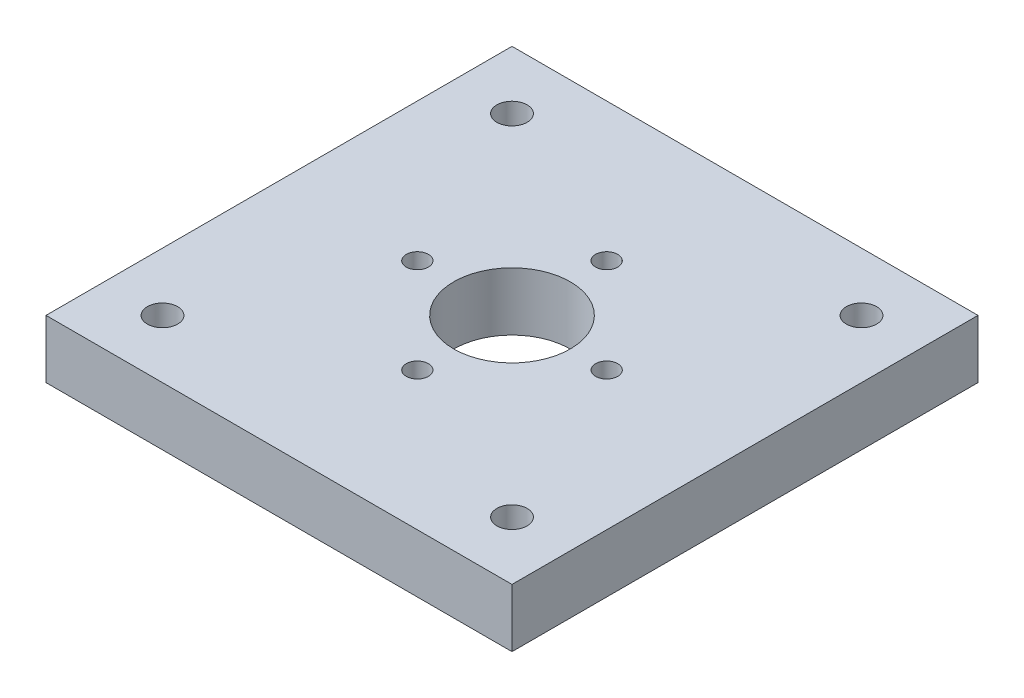
SolidWorks part; units mm, degrees
ref_plane "Front Plane" through (0, 0, 0) normal (0, 0, 1) x (1, 0, 0)
ref_plane "Top Plane" through (0, 0, 0) normal (0, 1, 0) x (1, 0, 0)
ref_plane "Right Plane" through (0, 0, 0) normal (1, 0, 0) x (0, 0, -1)
sketch "Sketch1" plane through (0, 0, 0) normal (0, 1, 0) x (1, 0, 0)
  line L0 (0, 24.4231) -> (0, -30.107) construction
  line L1 (-50.8, -50.8) -> (50.8, -50.8)
  line L2 (-50.8, -50.8) -> (-50.8, 50.8)
  line L3 (-50.8, 50.8) -> (50.8, 50.8)
  line L4 (50.8, -50.8) -> (50.8, 50.8)
  line L5 (-50.8, -50.8) -> (50.8, 50.8) construction
  line L6 (-50.8, 50.8) -> (50.8, -50.8) construction
  line L7 (-20.0713, 0) -> (21.8476, 0) construction
  circle A0 centre (-38.1, 38.1) radius 3.302
  circle A1 centre (-38.1, -38.1) radius 3.302
  circle A3 centre (38.1, -38.1) radius 3.302
  circle A4 centre (38.1, 38.1) radius 3.302
  circle A5 centre (0, 0) radius 12.7
  circle A6 centre (0, 20.6375) radius 2.413
  circle A7 centre (0, -20.6375) radius 2.413
  circle A8 centre (-20.6375, 0) radius 2.413
  circle A9 centre (20.6375, 0) radius 2.413
  point P0 (0, 0)
  dimension "D3" = 6.604
  dimension "D4" = 25.4
  dimension "D6" = 41.275
  dimension "D7" = 4.826
  dimension "D8" = 4.826
  dimension "D1" = 101.6
  dimension "D2" = 101.6
  dimension "D5" = 76.2
  dimension "D9" = 41.275
extrude "Boss-Extrude1" add sketch "Sketch1" along normal mid plane 12.7
